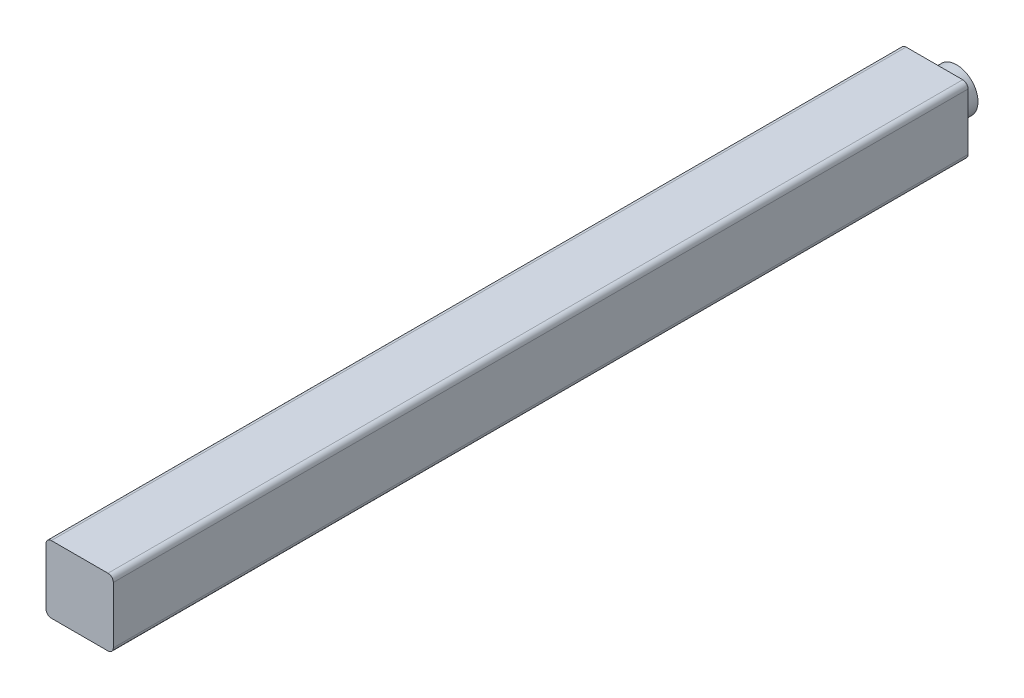
SolidWorks part; units mm, degrees
ref_plane "Front" through (0, 0, 0) normal (0, 0, 1) x (1, 0, 0)
ref_plane "Top" through (0, 0, 0) normal (0, 1, 0) x (1, 0, 0)
ref_plane "Right" through (0, 0, 0) normal (1, 0, 0) x (0, 0, -1)
sketch "Sketch2" plane through (0, 0, 0) normal (0, 0, 1) x (1, 0, 0)
  line L1 (0.25, 0) -> (2.9, 0)
  line L2 (0, 0.25) -> (0, 2.9)
  line L3 (0.25, 3.15) -> (2.9, 3.15)
  line L4 (3.15, 0.25) -> (3.15, 2.9)
  arc A0 (2.9, 0) -> (3.15, 0.25) centre (2.9, 0.25) ccw
  arc A1 (0, 0.25) -> (0.25, 0) centre (0.25, 0.25) ccw
  arc A2 (2.9, 3.15) -> (3.15, 2.9) centre (2.9, 2.9) cw
  arc A3 (0.25, 3.15) -> (0, 2.9) centre (0.25, 2.9) ccw
  point P9 (0, 0)
  dimension "D1" = 0.25
  dimension "D2" = 3.15
  dimension "D3" = 3.15
extrude "Boss-Extrude1" add sketch "Sketch2" along normal blind 40
sketch "Sketch3" plane through (0, 0, 0) normal (0, 0, -1) x (-1, 0, 0)
  circle A0 centre (-1.615, 1.615) radius 1
extrude "Boss-Extrude2" add sketch "Sketch3" along normal blind 1
